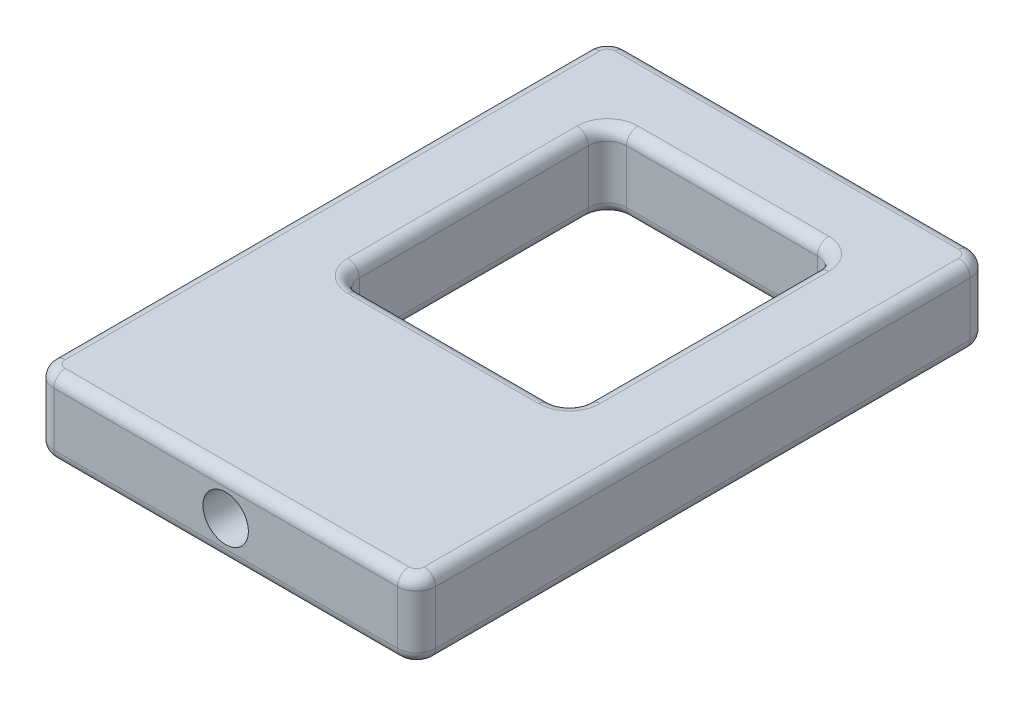
SolidWorks part; units mm, degrees
ref_plane "Front Plane" through (0, 0, 0) normal (0, 0, 1) x (1, 0, 0)
ref_plane "Top Plane" through (0, 0, 0) normal (0, 1, 0) x (1, 0, 0)
ref_plane "Right Plane" through (0, 0, 0) normal (1, 0, 0) x (0, 0, -1)
sketch "Sketch1" plane through (0, 0, 0) normal (0, 1, 0) x (1, 0, 0)
  line L1 (-12.7, 19.05) -> (12.7, 19.05)
  line L2 (-12.7, 19.05) -> (-12.7, -19.05)
  line L3 (-12.7, -19.05) -> (12.7, -19.05)
  line L4 (12.7, 19.05) -> (12.7, -19.05)
  line L5 (-12.7, 19.05) -> (12.7, -19.05) construction
  line L6 (-12.7, -19.05) -> (12.7, 19.05) construction
  point P0 (0, 0)
  dimension "D1" = 25.4
  dimension "D2" = 38.1
extrude "Boss-Extrude1" add sketch "Sketch1" along normal blind 5.08
sketch "Sketch2" plane through (0, 0, 0) normal (0, -1, 0) x (1, 0, 0)
  line L0 (12.7, -19.05) -> (-12.7, -19.05) construction
  line L1 (-7.62, -13.97) -> (7.62, -13.97)
  line L2 (-7.62, -13.97) -> (-7.62, 3.81)
  line L3 (-7.62, 3.81) -> (7.62, 3.81)
  line L4 (7.62, -13.97) -> (7.62, 3.81)
  line L5 (-7.62, -13.97) -> (7.62, 3.81) construction
  line L6 (-7.62, 3.81) -> (7.62, -13.97) construction
  line L7 (12.7, 19.05) -> (12.7, -19.05) construction
  line L8 (-12.7, -19.05) -> (-12.7, 19.05) construction
  line L9 (-12.7, 19.05) -> (12.7, 19.05) construction
  point P0 (0, -5.08)
  dimension "D1" = 5.08
  dimension "D2" = 5.08
  dimension "D3" = 5.08
  dimension "D4" = 15.24
extrude "Cut-Extrude1" cut sketch "Sketch2" against normal through all
sketch "Sketch3" plane through (0, 0, 19.05) normal (0, 0, 1) x (1, 0, 0)
  line L0 (0, 0) -> (0, 5.08) construction
  line L1 (-12.7, 5.08) -> (12.7, 5.08) construction
  line L2 (12.7, 2.54) -> (-12.7, 2.54) construction
  line L3 (12.7, 5.08) -> (12.7, 0) construction
  line L4 (-12.7, 5.08) -> (-12.7, 0) construction
  circle A0 centre (0, 2.54) radius 1.5113
extrude "Cut-Extrude3" cut sketch "Sketch3" against normal blind 7.62
fillet "Fillet1" radius 1.27 4 edges at (12.7, 2.54, -19.05) (-12.7, 2.54, -19.05) (-12.7, 2.54, 19.05) (12.7, 2.54, 19.05)
fillet "Fillet2" radius 1.27 4 edges at (-7.62, 2.54, -13.97) (7.62, 2.54, -13.97) (-7.62, 2.54, 3.81) (7.62, 2.54, 3.81)
fillet "Fillet3" radius 0.762 8 edges at (12.328, 5.08, 18.678) (0, 5.08, 19.05) (-12.328, 5.08, 18.678) (-12.7, 5.08, 0) (-12.328, 5.08, -18.678) (0, 5.08, -19.05) (12.328, 5.08, -18.678) (12.7, 5.08, 0)
fillet "Fillet4" radius 0.762 24 edges at (7.248, 5.08, 3.438) (7.62, 5.08, -5.08) (7.248, 5.08, -13.598) (0, 5.08, -13.97) (-7.248, 5.08, -13.598) (-7.62, 5.08, -5.08) (-7.248, 5.08, 3.438) (7.248, 0, 3.438) (7.62, 0, -5.08) (7.248, 0, -13.598) (0, 0, -13.97) (-7.248, 0, -13.598) (-7.62, 0, -5.08) (-7.248, 0, 3.438) (-12.328, 0, -18.678) (0, 0, -19.05) (12.328, 0, -18.678) (12.7, 0, 0) (12.328, 0, 18.678) (0, 0, 19.05) (-12.328, 0, 18.678) (0, 5.08, 3.81) (0, 0, 3.81) (-12.7, 0, 0)
